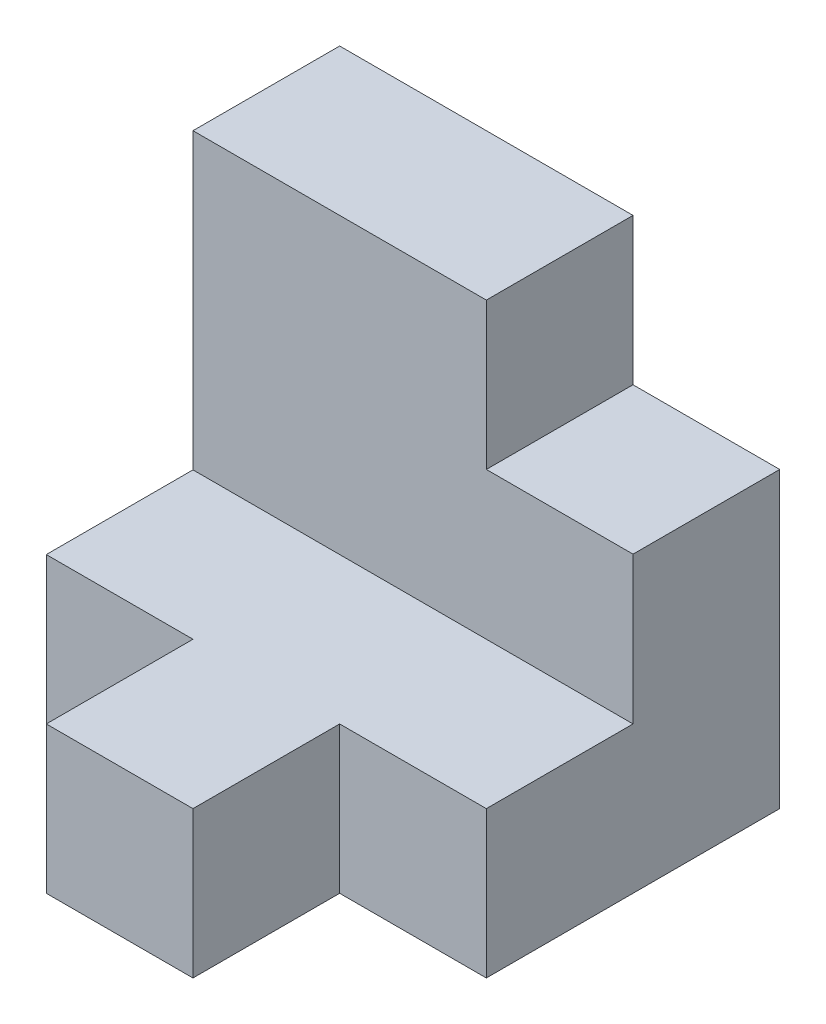
SolidWorks part; units mm, degrees
ref_plane "Plano frontal" through (0, 0, 0) normal (0, 0, 1) x (1, 0, 0)
ref_plane "Plano superior" through (0, 0, 0) normal (0, 1, 0) x (1, 0, 0)
ref_plane "Plano direito" through (0, 0, 0) normal (1, 0, 0) x (0, 0, -1)
sketch "Esboço2" plane through (0, 0, 0) normal (0, 0, 1) x (1, 0, 0)
  line L1 (0, 0) -> (60, 0)
  line L2 (0, 0) -> (0, 20)
  line L3 (0, 20) -> (60, 20)
  line L4 (60, 0) -> (60, 20)
  dimension "D1" = 60
  dimension "D2" = 20
extrude "Ressalto-extrusão1" add sketch "Esboço2" along normal blind 40
sketch "Esboço4" plane through (0, 20, 0) normal (0, 1, 0) x (1, 0, 0)
  line L1 (0, -40) -> (20, -40)
  line L2 (0, -40) -> (0, -20)
  line L3 (0, -20) -> (20, -20)
  line L4 (20, -40) -> (20, -20)
extrude "Corte-extrusão1" cut sketch "Esboço4" against normal blind 40
sketch "Esboço5" plane through (0, 20, 0) normal (0, 1, 0) x (1, 0, 0)
  line L1 (60, -40) -> (40, -40)
  line L2 (60, -40) -> (60, -20)
  line L3 (60, -20) -> (40, -20)
  line L4 (40, -40) -> (40, -20)
extrude "Corte-extrusão2" cut sketch "Esboço5" against normal blind 40
sketch "Esboço7" plane through (0, 0, 0) normal (0, 0, -1) x (-1, 0, 0)
  line L1 (-60, 0) -> (0, 0)
  line L2 (-60, 0) -> (-60, 40.0495)
  line L3 (-60, 40.0495) -> (0, 40.0495)
  line L4 (0, 0) -> (0, 40.0495)
extrude "Ressalto-extrusão2" add sketch "Esboço7" along normal blind 20
sketch "Esboço8" plane through (0, 40.0495, 0) normal (0, 1, 0) x (1, 0, 0)
  line L0 (60, 0) -> (0, 0) construction
  line L1 (0, 20) -> (40, 20)
  line L2 (0, 20) -> (0, 0)
  line L3 (0, 0) -> (40, 0)
  line L4 (40, 20) -> (40, 0)
  dimension "D1" = 40
extrude "Ressalto-extrusão3" add sketch "Esboço8" along normal blind 20
